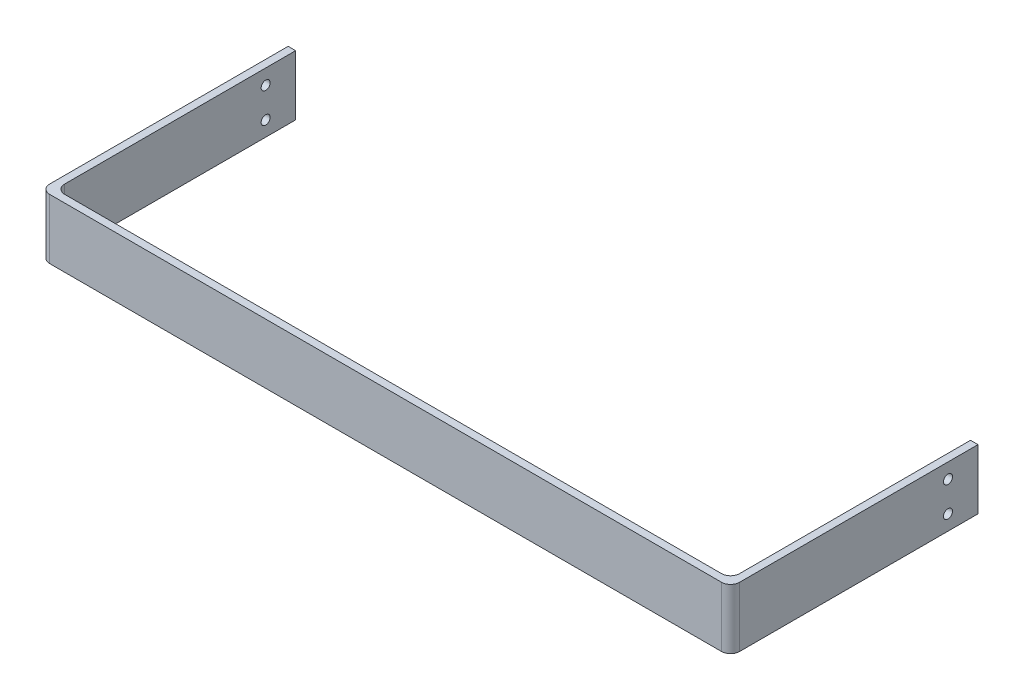
SolidWorks part; units mm, degrees
ref_plane "Front Plane" through (0, 0, 0) normal (0, 0, 1) x (1, 0, 0)
ref_plane "Top Plane" through (0, 0, 0) normal (0, 1, 0) x (1, 0, 0)
ref_plane "Right Plane" through (0, 0, 0) normal (1, 0, 0) x (0, 0, -1)
sketch "Sketch1" plane through (0, 0, 0) normal (0, 1, 0) x (1, 0, 0)
  line L0 (0, 80) -> (0, 0)
  line L1 (0, -55) -> (0, 55) construction
  line L2 (0, 0) -> (225, 0)
  line L3 (-55, 0) -> (55, 0) construction
  line L4 (225, 0) -> (225, 80)
  dimension "D1" = 225
  dimension "D2" = 80
extrude "Extrude-Thin1" add sketch "Sketch1" along normal blind 20 thin
fillet "Fillet1" radius 3 4 edges at (225, 10, 0) (227.5, 10, 2.5) (0, 10, 0) (-2.5, 10, 2.5)
sketch "Sketch2" plane through (-2.5, 0, 0) normal (1, 0, 0) x (0, 0, -1)
  line L0 (0.5, 20) -> (80, 20) construction
  line L1 (80, 20) -> (80, 0) construction
  circle A0 centre (70, 15) radius 1.5
  circle A1 centre (70, 5) radius 1.5
  dimension "D1" = 5
  dimension "D2" = 10
  dimension "D3" = 3
  dimension "D4" = 10
extrude "Cut-Extrude1" cut sketch "Sketch2" along normal blind 270
